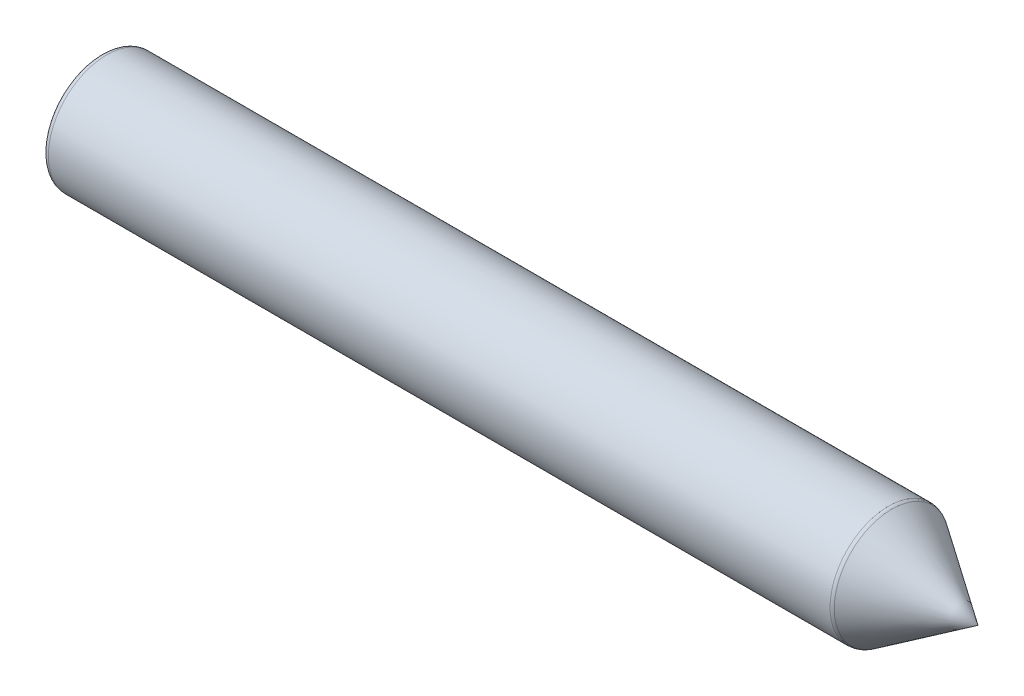
SolidWorks part; units mm, degrees
ref_plane "Front Plane" through (0, 0, 0) normal (0, 0, 1) x (1, 0, 0)
ref_plane "Top Plane" through (0, 0, 0) normal (0, 1, 0) x (1, 0, 0)
ref_plane "Right Plane" through (0, 0, 0) normal (1, 0, 0) x (0, 0, -1)
sketch "Sketch1" plane through (0, 0, 0) normal (0, 1, 0) x (1, 0, 0)
  line L0 (0, 0) -> (0, 10)
  line L1 (0, 10) -> (135, 10)
  line L2 (0, 0) -> (150, 0)
  line L3 (135, 10) -> (150, 0)
  dimension "D1" = 10
  dimension "D2" = 135
  dimension "D3" = 150
revolve "Revolve1" add sketch "Sketch1" angle 360 about L2
fillet "Fillet1" radius 1 2 edges at (135, 0, 10) (0, 0, 10)
